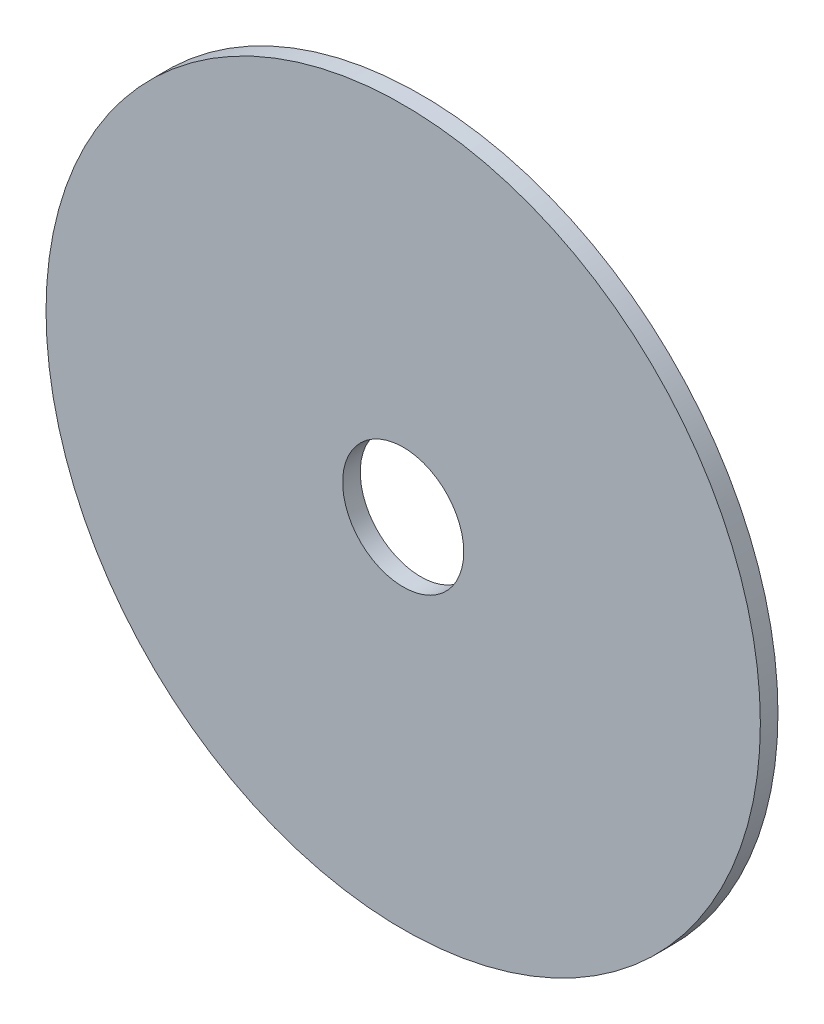
SolidWorks part; units mm, degrees
ref_plane "Front Plane" through (0, 0, 0) normal (0, 0, 1) x (1, 0, 0)
ref_plane "Top Plane" through (0, 0, 0) normal (0, 1, 0) x (1, 0, 0)
ref_plane "Right Plane" through (0, 0, 0) normal (1, 0, 0) x (0, 0, -1)
sketch "Sketch1" plane through (0, 0, 0) normal (0, 0, 1) x (1, 0, 0)
  circle A0 centre (0, 0) radius 64.39
  circle A1 centre (0, 0) radius 10.9163
extrude "Boss-Extrude1" add sketch "Sketch1" along normal blind 3.175 contours A0 A1
